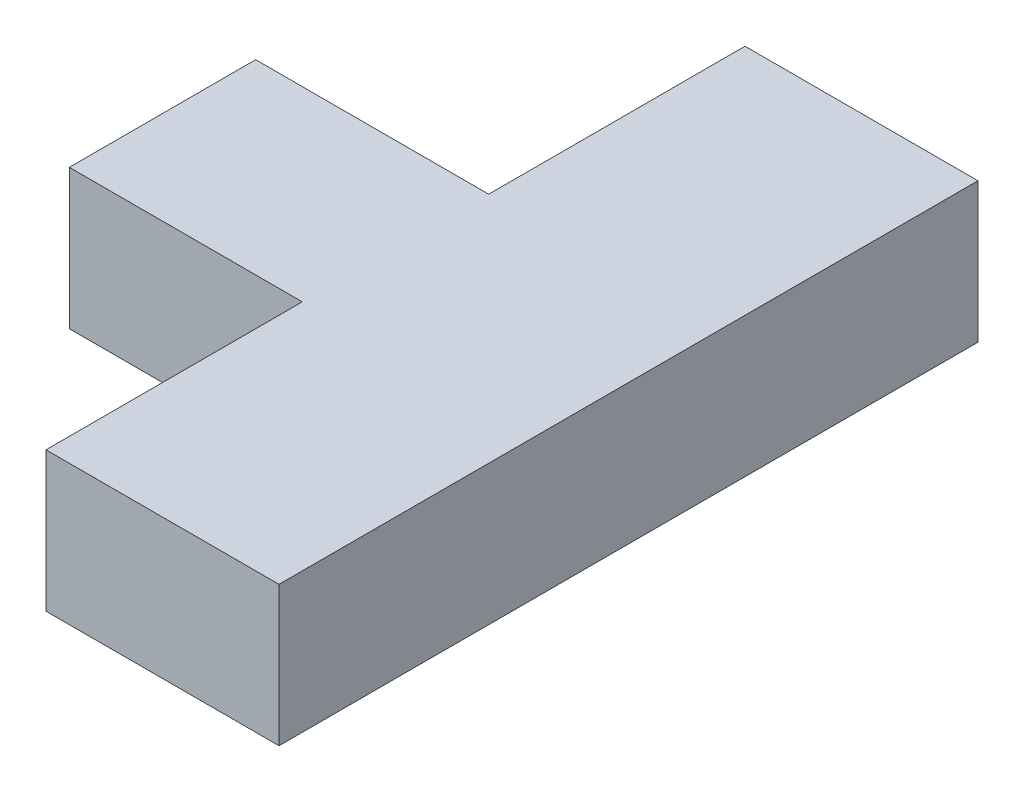
SolidWorks part; units mm, degrees
ref_plane "Front Plane" through (0, 0, 0) normal (0, 0, 1) x (1, 0, 0)
ref_plane "Top Plane" through (0, 0, 0) normal (0, 1, 0) x (1, 0, 0)
ref_plane "Right Plane" through (0, 0, 0) normal (1, 0, 0) x (0, 0, -1)
sketch "Sketch1" plane through (0, 0, 0) normal (0, 1, 0) x (1, 0, 0)
  line L1 (0, 1.5) -> (-0.5, 1.5)
  line L2 (-0.5, 1.5) -> (-0.5, 0.95)
  line L3 (-0.5, 0.95) -> (-1, 0.95)
  line L4 (-1, 0.95) -> (-1, 0.55)
  line L5 (-1, 0.55) -> (-0.5, 0.55)
  line L6 (-0.5, 0.55) -> (-0.5, 0)
  line L7 (-0.5, 0) -> (0, 0)
  line L8 (0, 1.5) -> (0, 0)
  point P3 (-1, 0.75)
  point P10 (0, 0.75)
  dimension "D1" = 0.5
  dimension "D2" = 1.5
  dimension "D3" = 0.4
  dimension "D4" = 0.5
extrude "Boss-Extrude1" add sketch "Sketch1" along normal blind 0.3
equation "\"t\"= 0.3'thickness of the sheets"
equation "\"FlexJoint\"= 0.15'Width of flextures"
equation "\"FoldJoint\"= 0.4'Width of folding joints"
equation "\"AssembleAngle\"= 90'Angle of assembly parts"
equation "\"D1@Boss-Extrude1\"=\"t\""
